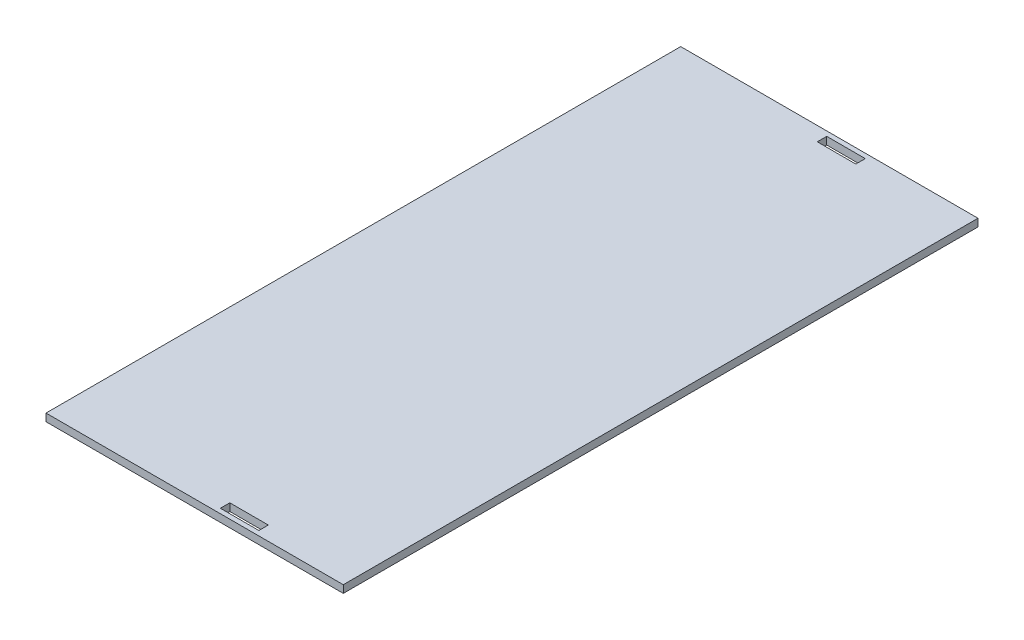
SolidWorks part; units mm, degrees
ref_plane "Front Plane" through (0, 0, 0) normal (0, 0, 1) x (1, 0, 0)
ref_plane "Top Plane" through (0, 0, 0) normal (0, 1, 0) x (1, 0, 0)
ref_plane "Right Plane" through (0, 0, 0) normal (1, 0, 0) x (0, 0, -1)
sketch "Sketch1" plane through (0, 0, 0) normal (0, 1, 0) x (1, 0, 0)
  line L1 (-39.345, 84) -> (39.345, 84)
  line L2 (-39.345, 84) -> (-39.345, -84)
  line L3 (-39.345, -84) -> (39.345, -84)
  line L4 (39.345, 84) -> (39.345, -84)
  line L5 (-39.345, 84) -> (39.345, -84) construction
  line L6 (-39.345, -84) -> (39.345, 84) construction
  point P0 (0, 0)
  dimension "D1" = 168
  dimension "D2" = 78.69
extrude "Boss-Extrude1" add sketch "Sketch1" along normal blind 2
sketch "Sketch2" plane through (0, 2, 0) normal (0, 1, 0) x (1, 0, 0)
  line L0 (39.345, 82.75) -> (-39.345, 82.75) construction
  line L1 (10.755, 82.75) -> (0.555, 82.75)
  line L2 (39.345, 84) -> (39.345, 82.75) construction
  line L3 (39.345, -84) -> (39.345, 84) construction
  line L4 (-39.345, 84) -> (-39.345, -84) construction
  line L5 (10.755, 82.75) -> (10.755, 80.25)
  line L6 (10.755, 80.25) -> (0.555, 80.25)
  line L7 (0.555, 82.75) -> (0.555, 80.25)
  dimension "D1" = 39.9
  dimension "D2" = 1.25
  dimension "D3" = 10.2
  dimension "D4" = 2.5
extrude "Cut-Extrude1" cut sketch "Sketch2" against normal blind 5
sketch "Sketch3" plane through (0, 2, 0) normal (0, 1, 0) x (1, 0, 0)
  line L0 (-39.345, -84) -> (-39.345, -82.75) construction
  line L1 (-39.345, 84) -> (-39.345, -84) construction
  line L2 (-39.345, -82.75) -> (5.5512, -82.75) construction
  line L3 (15.7512, -82.75) -> (39.345, -82.75) construction
  line L4 (5.5512, -82.75) -> (15.7512, -82.75)
  line L5 (5.5512, -82.75) -> (5.5512, -80.25)
  line L6 (5.5512, -80.25) -> (15.7512, -80.25)
  line L7 (15.7512, -82.75) -> (15.7512, -80.25)
  line L8 (39.345, -84) -> (39.345, 84) construction
  dimension "D1" = 1.25
  dimension "D2" = 23.5938
  dimension "D3" = 10.2
  dimension "D4" = 2.5
extrude "Cut-Extrude2" cut sketch "Sketch3" against normal blind 2
